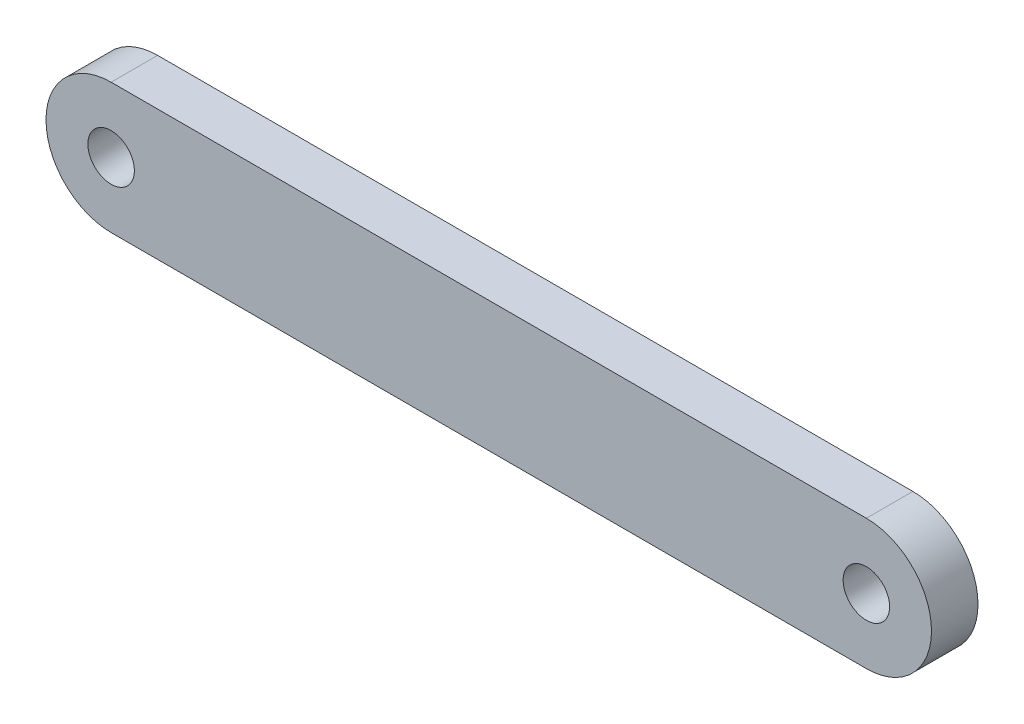
SolidWorks part; units mm, degrees
ref_plane "Front Plane" through (0, 0, 0) normal (0, 0, 1) x (1, 0, 0)
ref_plane "Top Plane" through (0, 0, 0) normal (0, 1, 0) x (1, 0, 0)
ref_plane "Right Plane" through (0, 0, 0) normal (1, 0, 0) x (0, 0, -1)
sketch "Sketch1" plane through (0, 0, 0) normal (0, 0, 1) x (1, 0, 0)
  line L0 (-18.7122, -8.6365) -> (84.3864, -8.6365)
  line L1 (-18.7122, 9.1435) -> (84.3864, 9.1435)
  line L2 (-18.7122, -8.6365) -> (84.3864, 9.1435) construction
  line L3 (-18.7122, 9.1435) -> (84.3864, -8.6365) construction
  arc A0 (-18.7122, 9.1435) -> (-18.7122, -8.6365) centre (-18.7122, 0.2535) ccw
  arc A1 (84.3864, 9.1435) -> (84.3864, -8.6365) centre (84.3864, 0.2535) cw
  circle A2 centre (-18.7122, 0.2535) radius 3.175
  circle A3 centre (84.3864, 0.2535) radius 3.175
  point P0 (32.8371, 0.2535)
  dimension "D3" = 6.35
  dimension "D1" = 103.0986
  dimension "D2" = 17.78
extrude "Boss-Extrude1" add sketch "Sketch1" along normal blind 6.35
